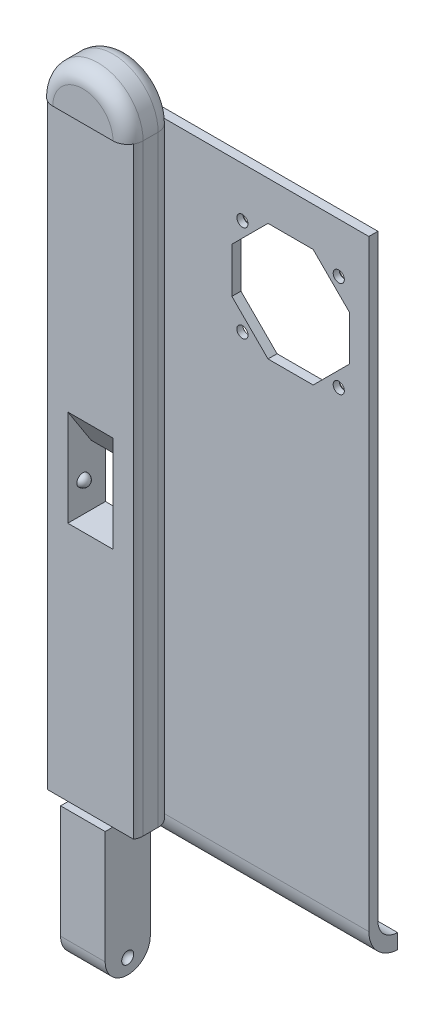
SolidWorks part; units mm, degrees
ref_plane "Front Plane" through (0, 0, 0) normal (0, 0, 1) x (1, 0, 0)
ref_plane "Top Plane" through (0, 0, 0) normal (0, 1, 0) x (1, 0, 0)
ref_plane "Right Plane" through (0, 0, 0) normal (1, 0, 0) x (0, 0, -1)
sketch "Sketch1" plane through (0, 0, 0) normal (0, 0, 1) x (1, 0, 0)
  line L0 (-7.4, -150) -> (7.4, -150)
  line L1 (7.4, -150) -> (7.4, -100)
  line L2 (7.4, -100) -> (15, -100)
  line L3 (15, -100) -> (15, 100)
  line L4 (-15, 100) -> (-15, -100)
  line L5 (-15, -100) -> (-7.4, -100)
  line L6 (-7.4, -100) -> (-7.4, -150)
  arc A0 (15, 100) -> (-15, 100) centre (0, 100) ccw
  point P7 (-15, 0)
  dimension "D2" = 14.8
  dimension "D3" = 15
  dimension "D1" = 250
  dimension "D4" = 15
  dimension "D5" = 50
extrude "Boss-Extrude1" add sketch "Sketch1" along normal mid plane 15
fillet "Fillet1" radius 5 8 edges at (15, 0, -7.5) (0, 115, -7.5) (15, 0, 7.5) (0, 115, 7.5) (-7.4, -150, 0) (7.4, -150, 0) (-15, 0, -7.5) (-15, 0, 7.5)
sketch "Sketch2" plane through (0, 0, 0) normal (0, 0, 1) x (1, 0, 0)
  line L0 (-23.2914, -140) -> (24.3018, -140) construction
  line L1 (-15, -100) -> (-10, -100) construction
  line L3 (-7.4, -100) -> (-7.4, -145) construction
  line L4 (-7.4, -138) -> (-7.4, -140)
  line L6 (7.4, -145) -> (7.4, -100) construction
  line L7 (7.4, -138) -> (7.4, -140)
  line L8 (-7.4, -140) -> (-5.4, -140)
  line L9 (7.4, -140) -> (5.4, -140)
  arc A2 (-5.4, -140) -> (-7.4, -138) centre (-7.4, -140) ccw
  arc A3 (5.4, -140) -> (7.4, -138) centre (7.4, -140) cw
  dimension "D1" = 40
  dimension "D2" = 2
  dimension "D3" = 2
sketch "Sketch3" plane through (0, 0, 0) normal (1, 0, 0) x (0, 0, -1)
  line L0 (7.5, -100) -> (7.5, 100) construction
  line L5 (17, -109.9875) -> (17, -104.9875)
  line L6 (10.5, -98.4875) -> (10.5, 100)
  line L7 (10.5, 100) -> (7.5, 100)
  line L8 (7.5, -100) -> (7.5, 100)
  arc A0 (7.5, -100) -> (17, -109.9875) centre (17.5, -100) ccw
  arc A1 (17, -104.9875) -> (10.5, -98.4875) centre (17, -98.4875) cw
  dimension "D1" = 10
  dimension "D4" = 6.5
  dimension "D2" = 3
  dimension "D3" = 5
sketch "Sketch4" plane through (0, 0, 7.5) normal (0, 0, 1) x (1, 0, 0)
  line L0 (-10, 100) -> (-10, -100) construction
  line L1 (-7.5, 0) -> (7.5, 0)
  line L2 (-7.5, 0) -> (-7.5, -20)
  line L3 (-7.5, -20) -> (7.5, -20)
  line L4 (7.5, 0) -> (7.5, -20)
  line L5 (-15, 100) -> (-10, 100) construction
  dimension "D1" = 20
  dimension "D2" = 15
  dimension "D3" = 2.5
extrude "Cut-Extrude1" cut sketch "Sketch4" against normal through all
sketch "Sketch5" plane through (0, 0, 0) normal (0, 0, 1) x (1, 0, 0)
  line L0 (-21.9659, -10) -> (20.5009, -10) construction
  line L1 (7.5, 0) -> (-7.5, 0) construction
  line L2 (-7.5, -10) -> (-5.5, -10)
  line L3 (-7.5, 0) -> (-7.5, -20) construction
  line L4 (-7.5, -8) -> (-7.5, -10)
  line L5 (7.5, -10) -> (5.5, -10)
  line L6 (7.5, -20) -> (7.5, 0) construction
  line L7 (7.5, -8) -> (7.5, -10)
  arc A0 (-5.5, -10) -> (-7.5, -8) centre (-7.5, -10) ccw
  arc A1 (5.5, -10) -> (7.5, -8) centre (7.5, -10) cw
  dimension "D1" = 10
  dimension "D2" = 2
  dimension "D3" = 2
revolve "Revolve2" add sketch "Sketch5" angle 360 about L0
revolve "Cut-Revolve1" cut sketch "Sketch2" angle 360 about L0
sketch "Sketch6" plane through (-7.4, 0, 0) normal (-1, 0, 0) x (0, 0, 1)
  line L0 (-7.5, -100) -> (-7.5, -145) construction
  line L1 (7.5, -100) -> (7.5, -145) construction
  line L2 (-7.5, -137.5) -> (-7.5, -150)
  line L3 (-7.5, -150) -> (7.5, -150)
  line L4 (7.5, -150) -> (-7.5, -150) construction
  line L5 (7.5, -150) -> (7.5, -137.5)
  line L6 (-7.5, -145) -> (7.5, -145) construction
  arc A0 (-7.5, -137.5) -> (7.5, -137.5) centre (0, -137.5) ccw
extrude "Cut-Extrude2" cut sketch "Sketch6" against normal through all
extrude "Boss-Extrude2" add sketch "Sketch3" along normal blind 80
sketch "Sketch7" plane through (0, 0, 0) normal (-1, 0, 0) x (0, 0, 1)
  line L0 (-10.5, 100) -> (-7.5, 100) construction
  line L1 (-7.5, 100) -> (-7.5, 0) construction
  line L2 (-7.5, 0) -> (-7.5, -20) construction
  line L3 (-7.5, -20) -> (-7.5, -100) construction
  line L4 (-17, -109.9875) -> (-17, -104.9875) construction
  line L5 (-10.5, -98.4875) -> (-10.5, 100) construction
  line L6 (-10.5, 100) -> (-7.5, 100)
  line L7 (-7.5, 100) -> (-7.5, 0)
  line L8 (-7.5, 0) -> (-7.5, -20)
  line L9 (-7.5, -20) -> (-7.5, -100)
  line L10 (-17, -109.9875) -> (-17, -104.9875)
  line L11 (-10.5, -98.4875) -> (-10.5, 100)
  arc A0 (-17, -109.9875) -> (-7.5, -100) centre (-17.5, -100) ccw construction
  arc A1 (-17, -104.9875) -> (-10.5, -98.4875) centre (-17, -98.4875) ccw construction
  arc A2 (-17, -109.9875) -> (-7.5, -100) centre (-17.5, -100) ccw
  arc A3 (-17, -104.9875) -> (-10.5, -98.4875) centre (-17, -98.4875) ccw
extrude "Boss-Extrude3" add sketch "Sketch7" along normal blind 5
sketch "Sketch9" plane through (0, 0, -10.5) normal (0, 0, -1) x (-1, 0, 0)
  line L0 (-7.5, -20) -> (-7.5, 0) construction
  line L1 (-7.5, -20) -> (-7.5, 0)
  line L2 (-7.5, 0) -> (5, 0) construction
  line L3 (5, -20) -> (-7.5, -20) construction
  line L4 (-7.5, 0) -> (5, 0)
  line L5 (5, -20) -> (-7.5, -20)
  line L6 (5, -20) -> (5, 0)
extrude "Cut-Extrude3" cut sketch "Sketch9" against normal blind 3
sketch "Sketch10" plane through (-15, 0, 0) normal (-1, 0, 0) x (0, 0, 1)
  line L0 (7.5, -100) -> (5, -100)
  line L1 (2.5, -100) -> (7.5, -100) construction
  line L2 (5, -100) -> (5, 100)
  line L3 (2.5, 100) -> (7.5, 100) construction
  line L4 (5, 100) -> (7.5, 100)
  line L5 (7.5, 100) -> (7.5, 110) construction
  line L6 (7.5, 100) -> (7.5, -100)
extrude "Cut-Extrude4" cut sketch "Sketch10" against normal through all
sketch "Sketch11" plane through (0, 0, -10.5) normal (0, 0, -1) x (-1, 0, 0)
  line L0 (-80, -98.4875) -> (5, -98.4875) construction
  line L1 (-46.5, 87.0125) -> (-61.5, 87.0125)
  line L2 (-61.5, 87.0125) -> (-73.5, 75.0125)
  line L3 (-73.5, 75.0125) -> (-73.5, 60.0125)
  line L4 (-73.5, 60.0125) -> (-61.5, 48.0125)
  line L5 (-61.5, 48.0125) -> (-46.5, 48.0125)
  line L6 (-46.5, 48.0125) -> (-34.5, 60.0125)
  line L7 (-34.5, 60.0125) -> (-34.5, 75.0125)
  line L8 (-34.5, 75.0125) -> (-46.5, 87.0125)
  line L9 (-80, -98.4875) -> (-80, 100) construction
  circle A1 centre (-38, 83.5125) radius 1.85
  circle A2 centre (-38, 51.5125) radius 1.85
  circle A3 centre (-70, 83.5125) radius 1.85
  circle A4 centre (-70, 51.5125) radius 1.85
  point P12 (-73.5, 67.5125)
  point P21 (-54, 87.0125)
  dimension "D1" = 32
  dimension "D8" = 3.7
  dimension "D9" = 16
  dimension "D2" = 32
  dimension "D3" = 32
  dimension "D4" = 150
  dimension "D5" = 39
  dimension "D6" = 15
  dimension "D7" = 39
  dimension "D10" = 10
  dimension "D11" = 16
extrude "Cut-Extrude5" cut sketch "Sketch11" against normal through all
sketch "Sketch12" plane through (0, 0, -10.5) normal (0, 0, -1) x (-1, 0, 0)
  circle A0 centre (-38, 83.5125) radius 3
  circle A1 centre (-70, 83.5125) radius 3
  circle A2 centre (-70, 51.5125) radius 3
  circle A3 centre (-38, 51.5125) radius 3.25
  dimension "D1" = 6
  dimension "D2" = 6
  dimension "D3" = 6
  dimension "D4" = 6.5
extrude "Cut-Extrude6" cut sketch "Sketch12" against normal blind 1
sketch "Sketch13" plane through (0, 0, 0) normal (1, 0, 0) x (0, 0, -1)
  line L0 (2.75, 0) -> (-5, 0)
  line L1 (10.5, 0) -> (-5, 0) construction
  line L2 (-5, -100) -> (-5, 100) construction
  line L3 (-5, 0) -> (-5, 12)
  line L4 (-5, 12) -> (2.75, 0)
  dimension "D1" = 12
extrude "Cut-Extrude7" cut sketch "Sketch13" against normal mid plane 15
